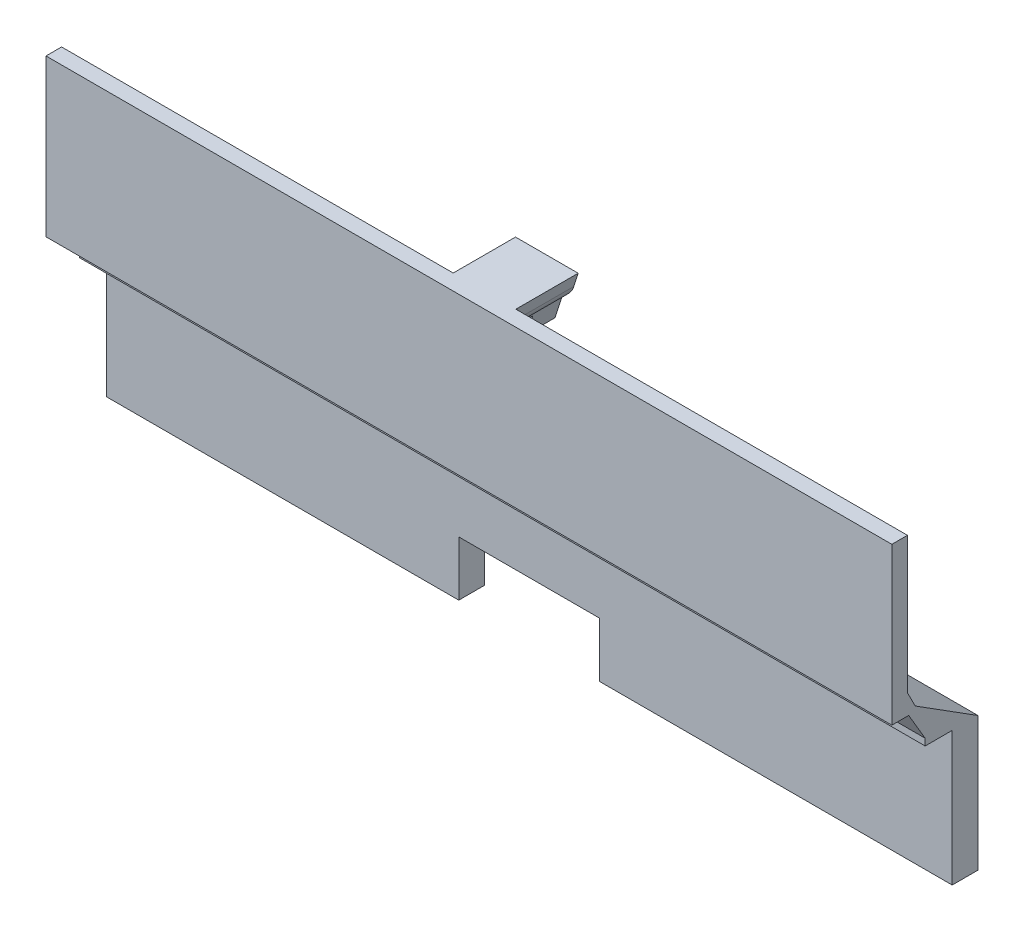
SolidWorks part; units mm, degrees
ref_plane "前视基准面" through (0, 0, 0) normal (0, 0, 1) x (1, 0, 0)
ref_plane "上视基准面" through (0, 0, 0) normal (0, 1, 0) x (1, 0, 0)
ref_plane "右视基准面" through (0, 0, 0) normal (1, 0, 0) x (0, 0, -1)
sketch "草图1" plane through (0, 0, 0) normal (1, 0, 0) x (0, 0, -1)
  line L0 (0, 20.187) -> (0, -21.4602) construction
  line L4 (5.5, -5.2349) -> (5.5, -1.2762)
  line L11 (5.5, 1.3032) -> (5.5, -1.2762)
  line L12 (0, 13.2651) -> (0, 9.0243)
  line L14 (0.9964, 13.35) -> (0.9964, 8.8815)
  line L16 (0, 13.2651) -> (0, 15.5311)
  line L17 (0, 15.5311) -> (0.9964, 15.5311)
  line L18 (0.9964, 15.5311) -> (0.9964, 13.35)
  line L19 (0, 9.0243) -> (0, 5.5311)
  line L20 (0, 5.5311) -> (1.076, 5.5311)
  line L21 (1.076, 5.5311) -> (2.1271, 3.7449)
  line L22 (2.1271, 3.7449) -> (2.1271, 3.316)
  line L23 (2.1271, 3.316) -> (3.852, 3.316)
  line L24 (3.852, 3.316) -> (3.852, -5.2349)
  line L25 (3.852, -5.2349) -> (5.5, -5.2349)
  line L26 (8.352, -5.2349) -> (3.852, -5.2349) construction
  line L27 (0.9964, 8.8815) -> (0.9964, 6.8227)
  line L28 (1.4957, 5.8417) -> (5.5, 3.316)
  line L29 (5.5, 3.316) -> (5.5, 1.3032)
  line L30 (0.9964, 6.8227) -> (1.4957, 5.8417)
  dimension "D1" = 10
  dimension "D3" = 1
extrude "凸台-拉伸1" add sketch "草图1" along normal mid plane 54 contours L4 L11 L29 L28 L30 L27 L14 L18 L17 L16 L12 L19 L20 L21 L22 L23 L24 L25
sketch "草图2" plane through (0, 0, -5.5) normal (0, 0, -1) x (-1, 0, 0)
  line L0 (0, 8.1951) -> (0, -10.3459) construction
  line L1 (-4.5, -5.7349) -> (-4.5, -1.7349)
  line L3 (-4.5, -1.7349) -> (4.5, -1.7349)
  line L4 (4.5, -1.7349) -> (4.5, -5.7349)
  line L5 (4.5, -5.7349) -> (-4.5, -5.7349)
  dimension "D1" = 9
  dimension "D2" = 4.5
extrude "切除-拉伸1" cut sketch "草图2" against normal blind 4
sketch "草图3" plane through (0, 0, -5.5) normal (0, 0, -1) x (-1, 0, 0)
  line L1 (4.5, -1.7349) -> (-4.5, -1.7349)
  line L2 (4.5, -1.7349) -> (4.5, 1.3032)
  line L3 (4.5, 1.3032) -> (-4.5, 1.3032)
  line L4 (-4.5, -1.7349) -> (-4.5, 1.3032)
extrude "凸台-拉伸2" add sketch "草图3" along normal blind 3
sketch "草图4" plane through (0, -1.7349, 0) normal (0, -1, 0) x (1, 0, 0)
  circle A0 centre (0, -6.102) radius 1.5
extrude "切除-拉伸2" cut sketch "草图4" against normal blind 9
sketch "草图6" plane through (0, 0, 0) normal (1, 0, 0) x (0, 0, -1)
  line L0 (0.9751, 15.5311) -> (4.9751, 15.5311)
  line L1 (4.9751, 15.5311) -> (4.9751, 12.3311)
  line L2 (4.9751, 12.3311) -> (3.1751, 12.3311)
  line L3 (3.1751, 12.3311) -> (3.1751, 13.5311)
  line L4 (3.1751, 13.5311) -> (2.0593, 13.5311)
  line L7 (2.0593, 13.5311) -> (0.9751, 13.5311)
  line L8 (0.9751, 13.5311) -> (0.9751, 15.5311)
  line L9 (0, 15.5311) -> (0.9964, 15.5311) construction
  dimension "D1" = 2
  dimension "D2" = 4
  dimension "D3" = 1.8
  dimension "D4" = 1.2
extrude "凸台-拉伸3" add sketch "草图6" along normal mid plane 4 contours L0 L1 L2 L3 L4 L7 L8
sketch "草图7" plane through (0, 0, -4.9751) normal (0, 0, -1) x (-1, 0, 0)
  line L0 (-2, 15.5311) -> (-1.7231, 14.6594)
  line L1 (-1, 13.8311) -> (-0.5234, 12.3311)
  line L2 (-2, 12.3311) -> (2, 12.3311) construction
  line L3 (0, 17.1262) -> (0, 11.4925) construction
  line L5 (-2, 15.5311) -> (2, 15.5311) construction
  line L8 (2, 15.5311) -> (1.7231, 14.6594)
  line L9 (1, 13.8311) -> (0.5234, 12.3311)
  line L10 (-2, 15.5311) -> (-2, 12.3311)
  line L11 (-2, 12.3311) -> (-0.5234, 12.3311)
  line L12 (0.5234, 12.3311) -> (2, 12.3311)
  line L13 (2, 12.3311) -> (2, 15.5311)
  arc A0 (-1.7231, 14.6594) -> (-1, 13.8311) centre (-0.4086, 15.0771) ccw
  arc A1 (1.7231, 14.6594) -> (1, 13.8311) centre (0.4086, 15.0771) cw
  point P13 (0, 15.5311)
  point P20 (0, 12.3311)
  line M5 (2, 12.3311) -> (2, 15.5311)
  line M8 (-2, 12.3311) -> (2, 12.3311)
  dimension "D1" = 1
  dimension "D2" = 1.7
extrude "切除-拉伸8" cut sketch "草图7" against normal blind 3.9 contours L8 A1 L9 M8 M5 | A0 L1 L11 L10 L0
